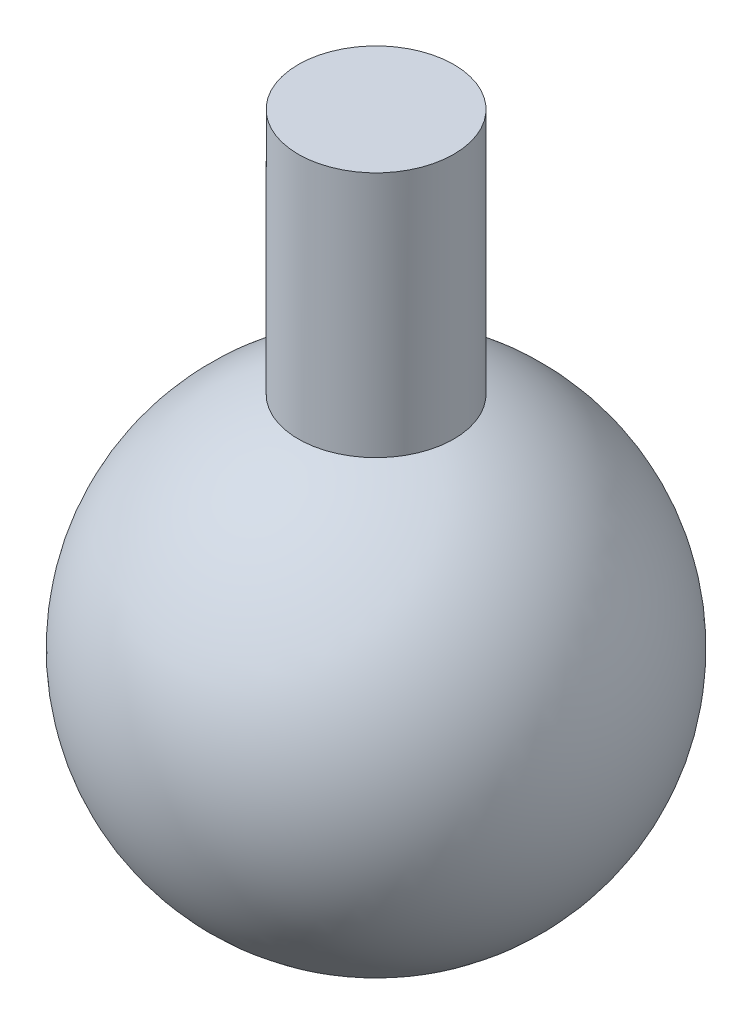
SolidWorks part; units mm, degrees
ref_plane "前视基准面" through (0, 0, 0) normal (0, 0, 1) x (1, 0, 0)
ref_plane "上视基准面" through (0, 0, 0) normal (0, 1, 0) x (1, 0, 0)
ref_plane "右视基准面" through (0, 0, 0) normal (1, 0, 0) x (0, 0, -1)
sketch "草图1" plane through (0, 0, 0) normal (0, 1, 0) x (1, 0, 0)
  line L0 (0, 3) -> (0, -3)
  arc A0 (0, -3) -> (0, 3) centre (0, 0) ccw
  dimension "D1" = 3
revolve "旋转1" add sketch "草图1" angle 360 about L0
sketch "草图2" plane through (0, 0, 0) normal (0, 1, 0) x (1, 0, 0)
  circle A0 centre (0, 0) radius 1
  dimension "D1" = 2
extrude "凸台-拉伸1" add sketch "草图2" along normal blind 6
